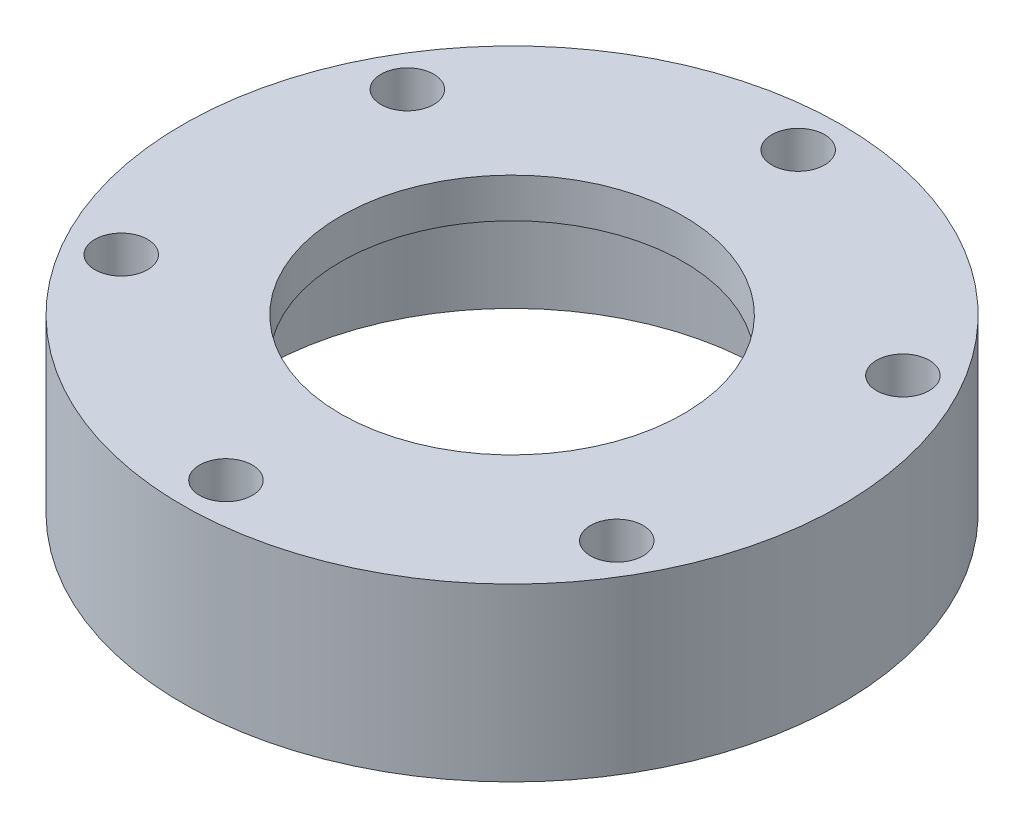
SolidWorks part; units mm, degrees
ref_plane "Спереди" through (0, 0, 0) normal (0, 0, 1) x (1, 0, 0)
ref_plane "Сверху" through (0, 0, 0) normal (0, 1, 0) x (1, 0, 0)
ref_plane "Справа" through (0, 0, 0) normal (1, 0, 0) x (0, 0, -1)
sketch "Эскиз1" plane through (0, 0, 0) normal (0, 1, 0) x (1, 0, 0)
  circle A0 centre (0, 0) radius 25
extrude "Вытянуть1" add sketch "Эскиз1" along normal blind 13
sketch "Эскиз3" plane through (0, 0, 0) normal (0, 1, 0) x (1, 0, 0)
  circle A0 centre (0, 21.7033) radius 2
  circle A1 centre (18.7956, 10.8516) radius 2
  circle A2 centre (18.7956, -10.8516) radius 2
  circle A3 centre (0, -21.7033) radius 2
  circle A4 centre (-18.7956, -10.8516) radius 2
  circle A5 centre (-18.7956, 10.8516) radius 2
extrude "Вытянуть3" cut sketch "Эскиз3" along normal through all
sketch "Эскиз4" plane through (0, 0, 0) normal (0, -1, 0) x (1, 0, 0)
  circle A0 centre (0, 0) radius 19
extrude "Вырез-Вытянуть1" cut sketch "Эскиз4" against normal blind 10
sketch "Эскиз5" plane through (0, 13, 0) normal (0, 1, 0) x (1, 0, 0)
  circle A0 centre (0, 0) radius 13
extrude "Вырез-Вытянуть2" cut sketch "Эскиз5" against normal through all
